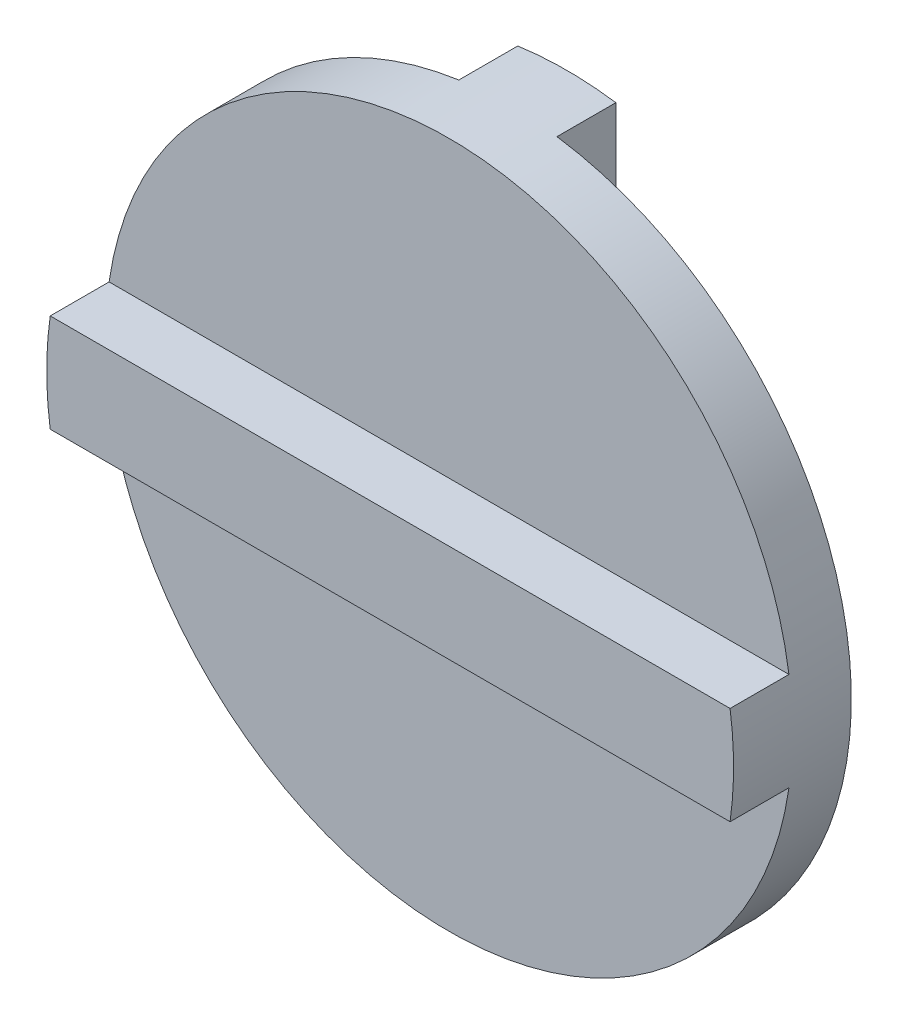
SolidWorks part; units mm, degrees
ref_plane "Front Plane" through (0, 0, 0) normal (0, 0, 1) x (1, 0, 0)
ref_plane "Top Plane" through (0, 0, 0) normal (0, 1, 0) x (1, 0, 0)
ref_plane "Right Plane" through (0, 0, 0) normal (1, 0, 0) x (0, 0, -1)
sketch "Sketch1" plane through (0, 0, 0) normal (0, 0, 1) x (1, 0, 0)
  circle A0 centre (0, 0) radius 12.25
  dimension "D1" = 24.5
extrude "Boss-Extrude1" add sketch "Sketch1" along normal mid plane 2.1
sketch "Sketch2" plane through (0, 0, 1.05) normal (0, 0, 1) x (1, 0, 0)
  line L1 (-12.1244, 1.75) -> (12.1244, 1.75)
  line L3 (-12.1244, -1.75) -> (12.1244, -1.75)
  line L5 (-12.1244, 1.75) -> (12.1244, -1.75) construction
  line L6 (-12.1244, -1.75) -> (12.1244, 1.75) construction
  arc A0 (12.1244, -1.75) -> (12.1244, 1.75) centre (0, 0) ccw
  circle A1 centre (0, 0) radius 12.25
  arc A2 (-12.1244, 1.75) -> (-12.1244, -1.75) centre (0, 0) ccw
  dimension "D2" = 3.5
  dimension "D1" = 0
extrude "Boss-Extrude2" add sketch "Sketch2" along normal blind 2.1
sketch "Sketch3" plane through (0, 0, -1.05) normal (0, 0, -1) x (-1, 0, 0)
  line L2 (-1.75, -12.1244) -> (-1.75, 12.1244)
  line L4 (1.75, -12.1244) -> (1.75, 12.1244)
  line L5 (-1.75, -12.1244) -> (1.75, 12.1244) construction
  line L6 (-1.75, 12.1244) -> (1.75, -12.1244) construction
  circle A0 centre (0, 0) radius 12.25 construction
  arc A1 (-1.75, -12.1244) -> (1.75, -12.1244) centre (0, 0) ccw
  arc A2 (1.75, 12.1244) -> (-1.75, 12.1244) centre (0, 0) ccw
  point P0 (0, 0)
  dimension "D1" = 3.5
extrude "Boss-Extrude3" add sketch "Sketch3" along normal blind 2.1
